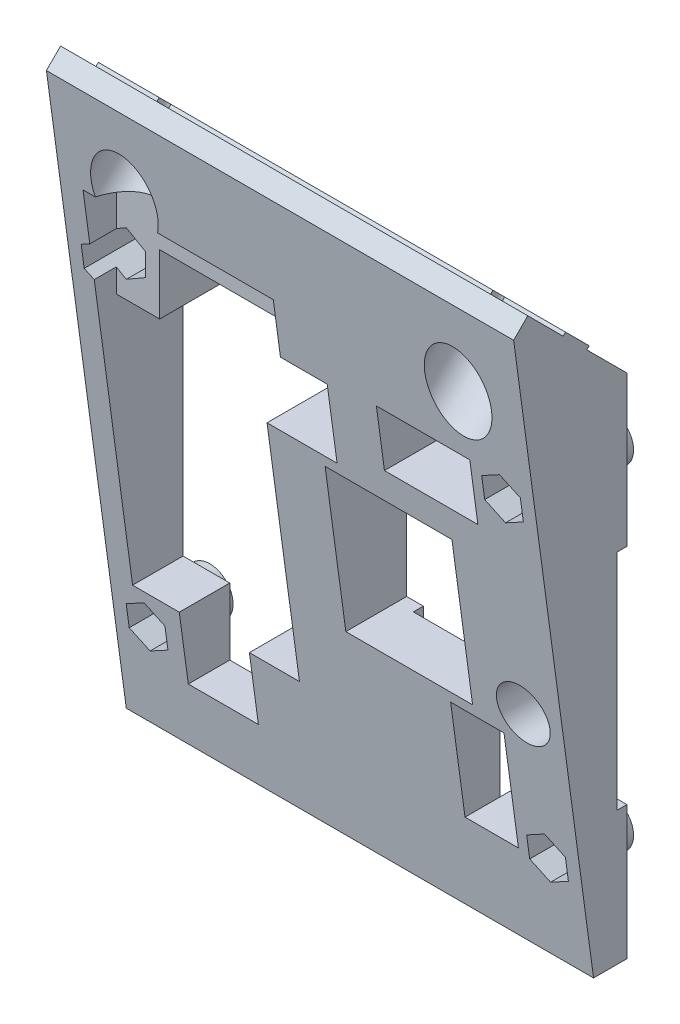
SolidWorks part; units mm, degrees
ref_plane "前视基准面" through (0, 0, 0) normal (0, 0, 1) x (1, 0, 0)
ref_plane "上视基准面" through (0, 0, 0) normal (0, 1, 0) x (1, 0, 0)
ref_plane "右视基准面" through (0, 0, 0) normal (1, 0, 0) x (0, 0, -1)
sketch "草图1" plane through (0, 0, 0) normal (1, 0, 0) x (0, 0, -1)
  line L0 (0, 0) -> (0, 76)
  line L1 (0, 76) -> (-14.8492, 90.8492)
  line L3 (-5, 0) -> (0, 0)
  line L4 (-14.8492, 90.8492) -> (-16.9706, 88.7279)
  line L5 (-16.9706, 88.7279) -> (-5, 0)
  dimension "D1" = 5
  dimension "D2" = 135
  dimension "D3" = 21
  dimension "D4" = 76
  dimension "D5" = 3
extrude "凸台-拉伸1" add sketch "草图1" along normal blind 90
sketch "草图2" plane through (0, 0, 0) normal (0, 0, -1) x (-1, 0, 0)
  line L0 (-90, 64) -> (0, 64) construction
  line L1 (-90, 0) -> (-90, 76) construction
  line L2 (0, 0) -> (0, 76) construction
  line L3 (-90, 14) -> (0, 14) construction
  line L4 (-75, 76) -> (-75, 0) construction
  line L5 (-90, 76) -> (0, 76) construction
  line L6 (-90, 0) -> (0, 0) construction
  line L7 (-15, 76) -> (-15, 0) construction
  circle A0 centre (-75, 64) radius 1.75
  circle A2 centre (-15, 64) radius 1.75
  circle A3 centre (-15, 14) radius 1.75
  circle A4 centre (-75, 14) radius 1.75
  dimension "D5" = 3.5
  dimension "D1" = 15
  dimension "D2" = 60
  dimension "D3" = 50
  dimension "D4" = 12
extrude "切除-拉伸1" cut sketch "草图2" against normal through all
sketch "草图3" plane through (0, 0, 0) normal (0, 0, -1) x (-1, 0, 0)
  line L0 (-90, 0) -> (-90, 76) construction
  line L1 (-38.5, 58) -> (-13.5, 58)
  line L2 (-38.5, 58) -> (-38.5, 19)
  line L3 (-38.5, 19) -> (-13.5, 19)
  line L4 (-13.5, 58) -> (-13.5, 19)
  line L5 (-20.5, 19) -> (-31, 19)
  line L6 (-20.5, 19) -> (-20.5, 9)
  line L7 (-20.5, 9) -> (-31, 9)
  line L8 (-31, 19) -> (-31, 9)
  line L9 (-20, 56) -> (-42, 56)
  line L10 (-20, 56) -> (-20, 67)
  line L11 (-20, 67) -> (-42, 67)
  line L12 (-42, 56) -> (-42, 67)
  line L13 (-49, 66) -> (-38, 66)
  line L14 (-49, 66) -> (-49, 55)
  line L15 (-49, 55) -> (-38, 55)
  line L16 (-38, 66) -> (-38, 55)
  line L17 (-70.5, 67) -> (-56.5, 67)
  line L18 (-70.5, 67) -> (-70.5, 58)
  line L19 (-70.5, 58) -> (-56.5, 58)
  line L20 (-56.5, 67) -> (-56.5, 58)
  line L21 (-90, 55) -> (-80.5, 55)
  line L22 (-90, 55) -> (-90, 13)
  line L23 (-90, 13) -> (-80.5, 13)
  line L24 (-80.5, 55) -> (-80.5, 13)
  line L25 (-90, 0) -> (0, 0) construction
  line L26 (-70.5, 13) -> (-62.5, 13)
  line L27 (-70.5, 13) -> (-70.5, 29)
  line L28 (-70.5, 29) -> (-62.5, 29)
  line L29 (-62.5, 13) -> (-62.5, 29)
  line L30 (-66, 30.5) -> (-47, 30.5)
  line L31 (-66, 30.5) -> (-66, 53.5)
  line L32 (-66, 53.5) -> (-47, 53.5)
  line L33 (-47, 30.5) -> (-47, 53.5)
  line L34 (0, 0) -> (0, 76) construction
  circle A0 centre (-15, 64) radius 1.75 construction
  circle A1 centre (-15, 64) radius 1.75 construction
  circle A2 centre (-75, 64) radius 1.75 construction
  circle A3 centre (-75, 14) radius 1.75 construction
  circle A4 centre (-15, 14) radius 1.75 construction
  circle A5 centre (-75, 64) radius 1.75 construction
  circle A6 centre (-75, 14) radius 1.75 construction
  circle A7 centre (-15, 14) radius 1.75 construction
  circle A8 centre (-74, 33.5) radius 4
  line M40 (-90, 76) -> (-90, 0)
  dimension "D22" = 8
  dimension "D1" = 39
  dimension "D2" = 6
  dimension "D3" = 1.5
  dimension "D4" = 25
  dimension "D5" = 5.5
  dimension "D6" = 16
  dimension "D7" = 10
  dimension "D8" = 2
  dimension "D9" = 11
  dimension "D10" = 5
  dimension "D11" = 22
  dimension "D12" = 49
  dimension "D13" = 1
  dimension "D14" = 11
  dimension "D15" = 11
  dimension "D16" = 9
  dimension "D17" = 4.5
  dimension "D18" = 14
  dimension "D19" = 5.5
  dimension "D20" = 1
  dimension "D21" = 42
  dimension "D23" = 4.5
  dimension "D24" = 1
  dimension "D25" = 8
  dimension "D26" = 16
  dimension "D27" = 19.5
  dimension "D28" = 1
  dimension "D29" = 19
  dimension "D30" = 23
  dimension "D31" = 24
  dimension "D32" = 30.5
extrude "切除-拉伸2" cut sketch "草图3" against normal through all contours L24 L21 L23 M40 | L20 L17 L18 L19 | L16 L13 L14 L15 | L12 L9 L2 L1 L10 L11 | L10 L9 L2 L3 L4 L1 | L9 L10 L1 L2 | L30 L33 L32 L31 | L3 L8 L7 L6 | L26 L29 L28 L27 | A8 | L16 L9 L2 L15 | L16 L1 L2 L9 | L16 L13 L12 L9 L2 L1
sketch "草图4" plane through (0, 0, 0) normal (0, 0, -1) x (-1, 0, 0)
  line L0 (-90, 0) -> (-90, 13) construction
  line L1 (-75, 60.6514) -> (-72.1, 62.3257)
  line L2 (-72.1, 62.3257) -> (-72.1, 65.6743)
  line L3 (-72.1, 65.6743) -> (-75, 67.3486)
  line L4 (-75, 67.3486) -> (-77.9, 65.6743)
  line L5 (-77.9, 65.6743) -> (-77.9, 62.3257)
  line L6 (-77.9, 62.3257) -> (-75, 60.6514)
  line L7 (-15, 60.6514) -> (-12.1, 62.3257)
  line L8 (-12.1, 62.3257) -> (-12.1, 65.6743)
  line L9 (-12.1, 65.6743) -> (-15, 67.3486)
  line L10 (-15, 67.3486) -> (-17.9, 65.6743)
  line L11 (-17.9, 65.6743) -> (-17.9, 62.3257)
  line L12 (-17.9, 62.3257) -> (-15, 60.6514)
  line L13 (-15, 10.6514) -> (-12.1, 12.3257)
  line L14 (-12.1, 12.3257) -> (-12.1, 15.6743)
  line L15 (-12.1, 15.6743) -> (-15, 17.3486)
  line L16 (-15, 17.3486) -> (-17.9, 15.6743)
  line L17 (-17.9, 15.6743) -> (-17.9, 12.3257)
  line L18 (-17.9, 12.3257) -> (-15, 10.6514)
  line L19 (-75, 10.6514) -> (-72.1, 12.3257)
  line L20 (-72.1, 12.3257) -> (-72.1, 15.6743)
  line L21 (-72.1, 15.6743) -> (-75, 17.3486)
  line L22 (-75, 17.3486) -> (-77.9, 15.6743)
  line L23 (-77.9, 15.6743) -> (-77.9, 12.3257)
  line L24 (-77.9, 12.3257) -> (-75, 10.6514)
  circle A4 centre (-75, 64) radius 2.9 construction
  circle A5 centre (-15, 64) radius 2.9 construction
  circle A6 centre (-15, 14) radius 2.9 construction
  circle A7 centre (-75, 14) radius 2.9 construction
  dimension "D1" = 5.8
extrude "切除-拉伸3" cut sketch "草图4" against normal up to next from offset 2 offset against normal yes
sketch "草图5" plane through (0, 0, 0) normal (0, 0, -1) x (-1, 0, 0)
  line L0 (-70.5, 13) -> (-70.5, 29) construction
  line L1 (-70.5, 30) -> (-80.5, 30)
  line L2 (-70.5, 30) -> (-70.5, 20)
  line L3 (-70.5, 20) -> (-80.5, 20)
  line L4 (-80.5, 30) -> (-80.5, 20)
  line L5 (-80.5, 55) -> (-80.5, 13) construction
  line L6 (-90, 0) -> (0, 0) construction
  line L7 (-80.5, 30) -> (-66, 30)
  line L8 (-80.5, 30) -> (-80.5, 53.5)
  line L9 (-80.5, 53.5) -> (-66, 53.5)
  line L10 (-66, 30) -> (-66, 53.5)
  line L11 (-62.5, 29) -> (-49.5, 29)
  line L12 (-62.5, 29) -> (-62.5, 0)
  line L13 (-62.5, 0) -> (-49.5, 0)
  line L14 (-49.5, 29) -> (-49.5, 0)
  line L15 (-66, 30.5) -> (-47, 30.5) construction
  line L16 (-70.5, 29) -> (-49.5, 29)
  line L17 (-70.5, 29) -> (-70.5, 30.5)
  line L18 (-70.5, 30.5) -> (-49.5, 30.5)
  line L19 (-49.5, 29) -> (-49.5, 30.5)
  circle A0 centre (-75, 14) radius 1.75 construction
  circle A1 centre (-75, 14) radius 1.75 construction
  circle M3 centre (-74, 33.5) radius 4
  line M4 (-62.5, 29) -> (-62.5, 13)
  line M6 (-70.5, 13) -> (-70.5, 29)
  line M14 (-66, 30.5) -> (-66, 53.5)
  line M16 (-80.5, 55) -> (-80.5, 13)
  line M19 (-90, 0) -> (0, 0)
  dimension "D1" = 10
  dimension "D2" = 6
  dimension "D3" = 13
extrude "切除-拉伸4" cut sketch "草图5" against normal blind 1.5 contours L7 L10 L9 L1 M14 M16 M3 | L3 L2 L1 M6 M3 M16 | L14 L11 L12 M4 M19 | L19 L18 L17 L16
sketch "草图6" plane through (0, 38, -38) normal (0, 0.7071, -0.7071) x (1, 0, 0)
  line L0 (0, -53.7401) -> (0, -74.7401) construction
  line L1 (0, -62.2401) -> (90, -62.2401)
  line L2 (0, -62.2401) -> (0, -67.2401)
  line L3 (0, -67.2401) -> (90, -67.2401)
  line L4 (90, -62.2401) -> (90, -67.2401)
  line L5 (90, -53.7401) -> (90, -74.7401) construction
  line L6 (0, -64.7401) -> (90, -64.7401) construction
  line L7 (90, -74.7401) -> (0, -74.7401) construction
  dimension "D1" = 10
  dimension "D2" = 5
extrude "凸台-拉伸2" add sketch "草图6" along normal blind 0.5
sketch "草图7" plane through (0, 38.3536, -38.3536) normal (0, 0.7071, -0.7071) x (1, 0, 0)
  line L0 (0, -64.7401) -> (90, -64.7401) construction
  line L1 (0, -62.2401) -> (0, -67.2401) construction
  line L2 (90, -67.2401) -> (90, -62.2401) construction
  line L3 (0, -67.2401) -> (0, -74.7401) construction
  line L4 (90, -67.2401) -> (90, -74.7401) construction
  circle A0 centre (20, -64.7401) radius 2.65
  circle A1 centre (70, -64.7401) radius 2.65
  dimension "D1" = 5.3
  dimension "D2" = 20
  dimension "D3" = 20
extrude "切除-拉伸5" cut sketch "草图7" against normal through all
sketch "草图8" plane through (0, 38.3536, -38.3536) normal (0, 0.7071, -0.7071) x (1, 0, 0)
  circle A0 centre (20, -64.7401) radius 5
  circle A1 centre (70, -64.7401) radius 5
  dimension "D1" = 10
extrude "切除-拉伸6" cut sketch "草图8" against normal up to next from offset 4 offset against normal yes
sketch "草图9" plane through (0, 0, 0) normal (0, 0, -1) x (-1, 0, 0)
  circle A0 centre (-75, 64) radius 3.5
  circle A1 centre (-15, 64) radius 3.5
  circle A2 centre (-15, 14) radius 3.5
  circle A3 centre (-75, 14) radius 3.5
  dimension "D1" = 7
extrude "凸台-拉伸3" add sketch "草图9" along normal blind 2.5
sketch "草图10" plane through (0, 0, -2.5) normal (0, 0, -1) x (-1, 0, 0)
  circle A1 centre (-75, 14) radius 1.75
  circle A2 centre (-75, 14) radius 1.75
  circle A3 centre (-15, 14) radius 1.75
  circle A4 centre (-15, 14) radius 1.75
  circle A5 centre (-15, 64) radius 1.75
  circle A6 centre (-15, 64) radius 1.75
  circle A7 centre (-75, 64) radius 1.75
  circle A8 centre (-75, 64) radius 1.75
  dimension "D1" = 0
  dimension "D2" = 0
  dimension "D3" = 0
  dimension "D4" = 0
extrude "切除-拉伸7" cut sketch "草图10" against normal through all
sketch "草图11" plane through (0, 0, 0) normal (0, 0, -1) x (-1, 0, 0)
  line L1 (-13.5, 74) -> (-42, 74)
  line L2 (-13.5, 74) -> (-13.5, 56)
  line L3 (-13.5, 56) -> (-42, 56)
  line L4 (-42, 74) -> (-42, 56)
  line L6 (-13.5, 58) -> (-13.5, 19) construction
  line L7 (-42, 66) -> (-42, 67) construction
  dimension "D1" = 18
extrude "切除-拉伸8" cut sketch "草图11" against normal up to next from offset 10 offset against normal yes
sketch "草图12" plane through (0, -0.6625, 4.9106) normal (0, -0.1337, 0.991) x (1, 0, 0)
  line L0 (90, 90.2003) -> (90, 56.1668) construction
  line L1 (0, 94.5051) -> (10, 94.5051)
  line L2 (0, 94.5051) -> (0, -3.84)
  line L3 (0, -3.84) -> (10, -3.84)
  line L4 (10, 94.5051) -> (10, -3.84)
  line L5 (90, 94.5051) -> (80, 94.5051)
  line L6 (90, 94.5051) -> (90, -6.5332)
  line L7 (90, -6.5332) -> (80, -6.5332)
  line L8 (80, 94.5051) -> (80, -6.5332)
  line L9 (0, 90.2003) -> (0, 0.6685) construction
  dimension "D1" = 10
  dimension "D2" = 10
extrude "切除-拉伸9" cut sketch "草图12" against normal through all
